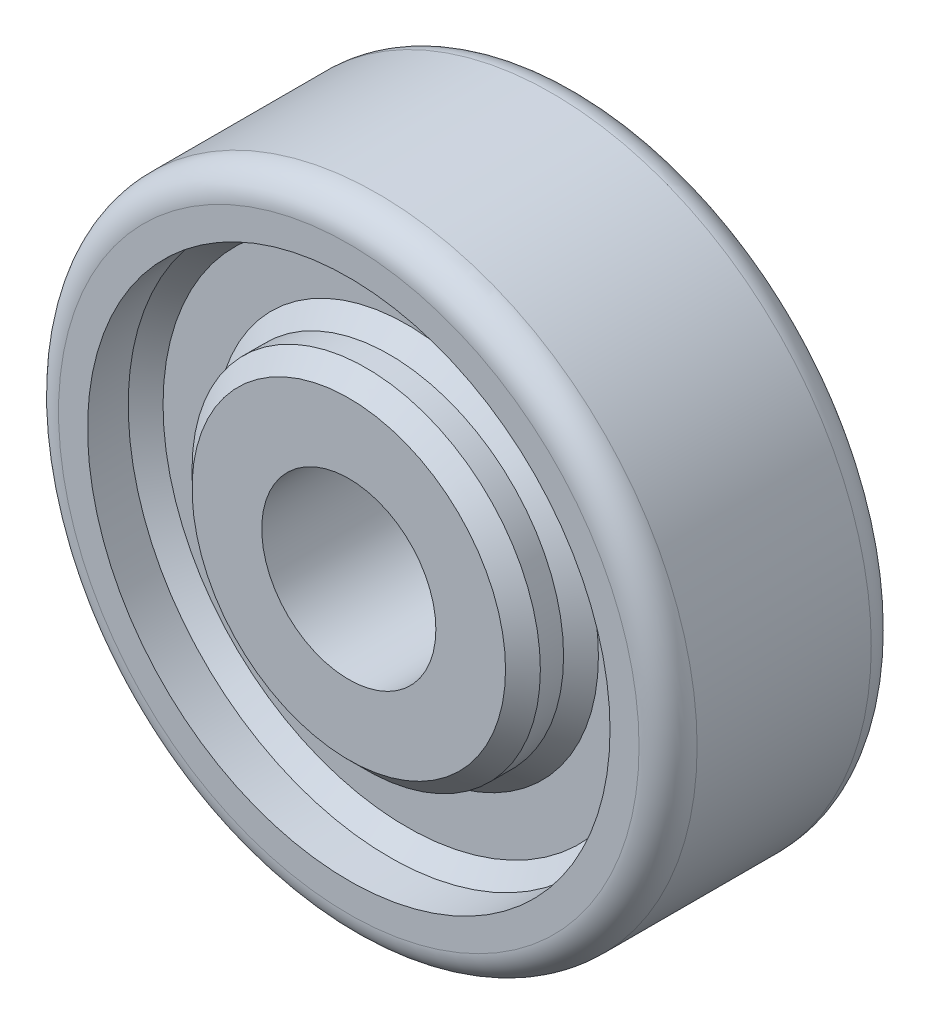
SolidWorks part; units mm, degrees
ref_plane "Front Plane" through (0, 0, 0) normal (0, 0, 1) x (1, 0, 0)
ref_plane "Top Plane" through (0, 0, 0) normal (0, 1, 0) x (1, 0, 0)
ref_plane "Right Plane" through (0, 0, 0) normal (1, 0, 0) x (0, 0, -1)
sketch "Sketch1" plane through (0, 0, 0) normal (0, 0, 1) x (1, 0, 0)
  circle A0 centre (0, 0) radius 55
  dimension "D1" = 110
extrude "Boss-Extrude1" add sketch "Sketch1" along normal mid plane 40
sketch "Sketch2" plane through (0, 0, 20) normal (0, 0, 1) x (1, 0, 0)
  circle A0 centre (0, 0) radius 45
  circle A1 centre (0, 0) radius 30
  dimension "D1" = 60
extrude "Cut-Extrude2" cut sketch "Sketch2" against normal blind 10 contours A0 | A1
mirror "Mirror1" about plane through (0, 0, 0) normal (0, 0, 1) of "Cut-Extrude2"
sketch "Sketch4" plane through (0, 0, 20) normal (0, 0, 1) x (1, 0, 0)
  circle A0 centre (0, 0) radius 15
  dimension "D1" = 30
extrude "Cut-Extrude3" cut sketch "Sketch4" against normal blind 87
fillet "Fillet1" radius 5 2 edges at (55, 0, -20) (55, 0, 20)
chamfer "Chamfer1" distance 3 angle 45 4 edges at (30, 0, -20) (45, 0, 10) (30, 0, 10) (30, 0, 20)
